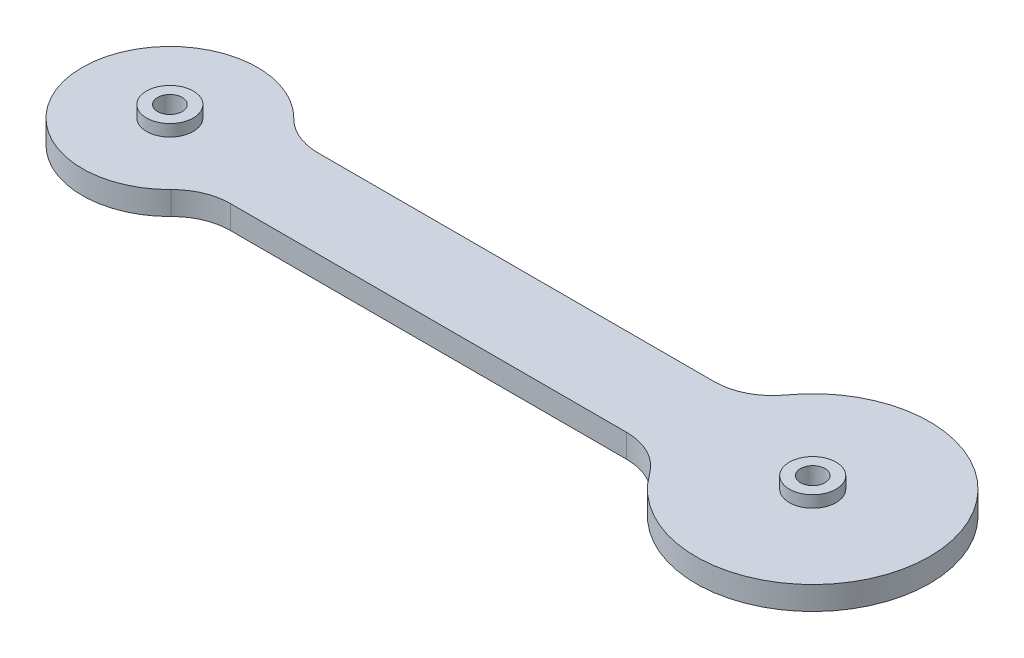
SolidWorks part; units mm, degrees
ref_plane "Front Plane" through (0, 0, 0) normal (0, 0, 1) x (1, 0, 0)
ref_plane "Top Plane" through (0, 0, 0) normal (0, 1, 0) x (1, 0, 0)
ref_plane "Right Plane" through (0, 0, 0) normal (1, 0, 0) x (0, 0, -1)
sketch "Sketch1" plane through (0, 0, 0) normal (0, 1, 0) x (1, 0, 0)
  line L1 (-42.0096, 7.5) -> (36.4595, 7.5)
  line L3 (-42.0096, -7.5) -> (36.4595, -7.5)
  arc A0 (-42.0096, 7.5) -> (-42.0096, -7.5) centre (-55, 0) ccw
  arc A1 (36.4595, -7.5) -> (36.4595, 7.5) centre (55, 0) ccw
  circle A2 centre (-55, 0) radius 2.1
  circle A3 centre (55, 0) radius 2.1
  point P0 (0, 0)
  dimension "D3" = 30
  dimension "D4" = 40
  dimension "D1" = 4.2
  dimension "D2" = 4.2
extrude "Boss-Extrude1" add sketch "Sketch1" along normal blind 4
fillet "Fillet1" radius 10 4 edges at (-42.0096, 2, -7.5) (36.4595, 2, -7.5) (36.4595, 2, 7.5) (-42.0096, 2, 7.5)
sketch "Sketch2" plane through (0, 4, 0) normal (0, 1, 0) x (1, 0, 0)
  circle A0 centre (55, 0) radius 4
  circle A1 centre (-55, 0) radius 4
  circle A2 centre (55, 0) radius 2.1
  circle A3 centre (-55, 0) radius 2.1
  dimension "D1" = 8
  dimension "D2" = 8
extrude "Boss-Extrude2" add sketch "Sketch2" along normal blind 2
